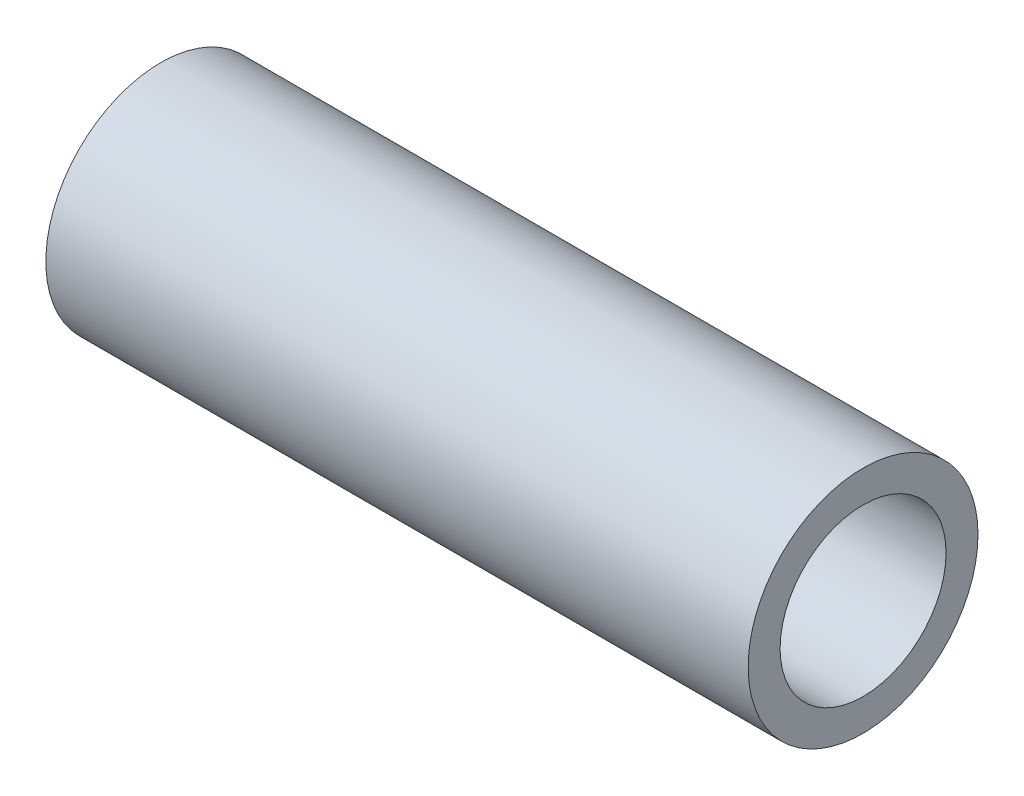
SolidWorks part; units mm, degrees
ref_plane "Front Plane" through (0, 0, 0) normal (0, 0, 1) x (1, 0, 0)
ref_plane "Top Plane" through (0, 0, 0) normal (0, 1, 0) x (1, 0, 0)
ref_plane "Right Plane" through (0, 0, 0) normal (1, 0, 0) x (0, 0, -1)
sketch "Sketch1" plane through (0, 0, 0) normal (1, 0, 0) x (0, 0, -1)
  circle A0 centre (0, 0) radius 9
  circle A1 centre (0, 0) radius 6.5
  dimension "D1" = 18
  dimension "D2" = 13
extrude "Boss-Extrude1" add sketch "Sketch1" along normal mid plane 55
